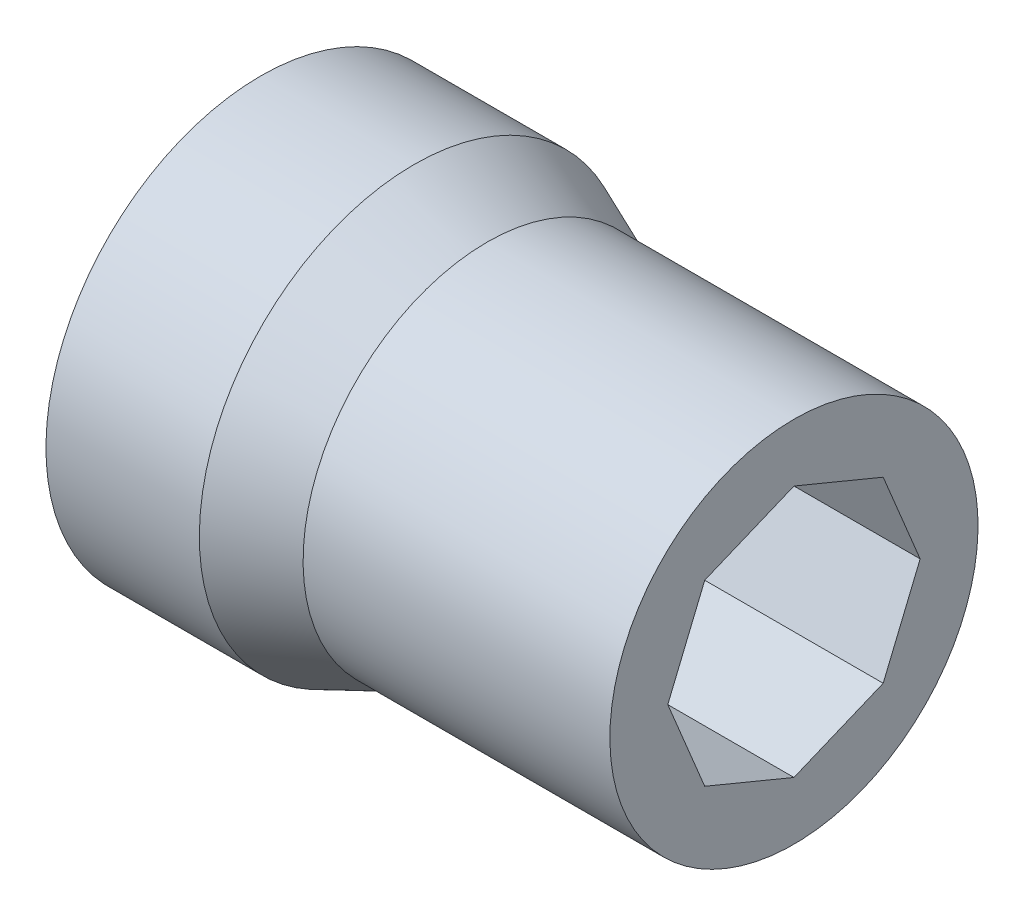
SolidWorks part; units mm, degrees
ref_plane "Front Plane" through (0, 0, 0) normal (0, 0, 1) x (1, 0, 0)
ref_plane "Top Plane" through (0, 0, 0) normal (0, 1, 0) x (1, 0, 0)
ref_plane "Right Plane" through (0, 0, 0) normal (1, 0, 0) x (0, 0, -1)
sketch "Sketch4" plane through (0, 0, 0) normal (0, 0, 1) x (1, 0, 0)
  line L0 (0, 0) -> (-5, 0)
  line L1 (-5, 0) -> (-5, 3.5)
  line L6 (-1.3094, 3) -> (0, 3)
  line L8 (-5, 3.5) -> (-2.5, 3.5)
  line L9 (-1.3094, 3) -> (-2.5, 3.5)
  line L10 (-1.3094, 3) -> (3.6906, 3) construction
  line L11 (-1.3094, 3) -> (3.6906, 3)
  line L12 (3.6906, 3) -> (3.6906, 0)
  line L13 (0, 0) -> (3.6906, 0)
  dimension "D1" = 3.5
  dimension "D2" = 3
  dimension "D3" = 3.5
revolve "Revolve4" add sketch "Sketch4" angle 360 about L0
sketch "Sketch6" plane through (3.6906, 0, 0) normal (1, 0, 0) x (0, 0, -1)
  line L1 (-2.0565, 0) -> (-1.4542, -1.4542)
  line L2 (-1.4542, -1.4542) -> (0, -2.0565)
  line L3 (0, -2.0565) -> (1.4542, -1.4542)
  line L4 (1.4542, -1.4542) -> (2.0565, 0)
  line L5 (2.0565, 0) -> (1.4542, 1.4542)
  line L6 (1.4542, 1.4542) -> (0, 2.0565)
  line L7 (0, 2.0565) -> (-1.4542, 1.4542)
  line L8 (-1.4542, 1.4542) -> (-2.0565, 0)
  circle A0 centre (0, 0) radius 1.9 construction
extrude "Cut-Extrude2" cut sketch "Sketch6" against normal blind 4
